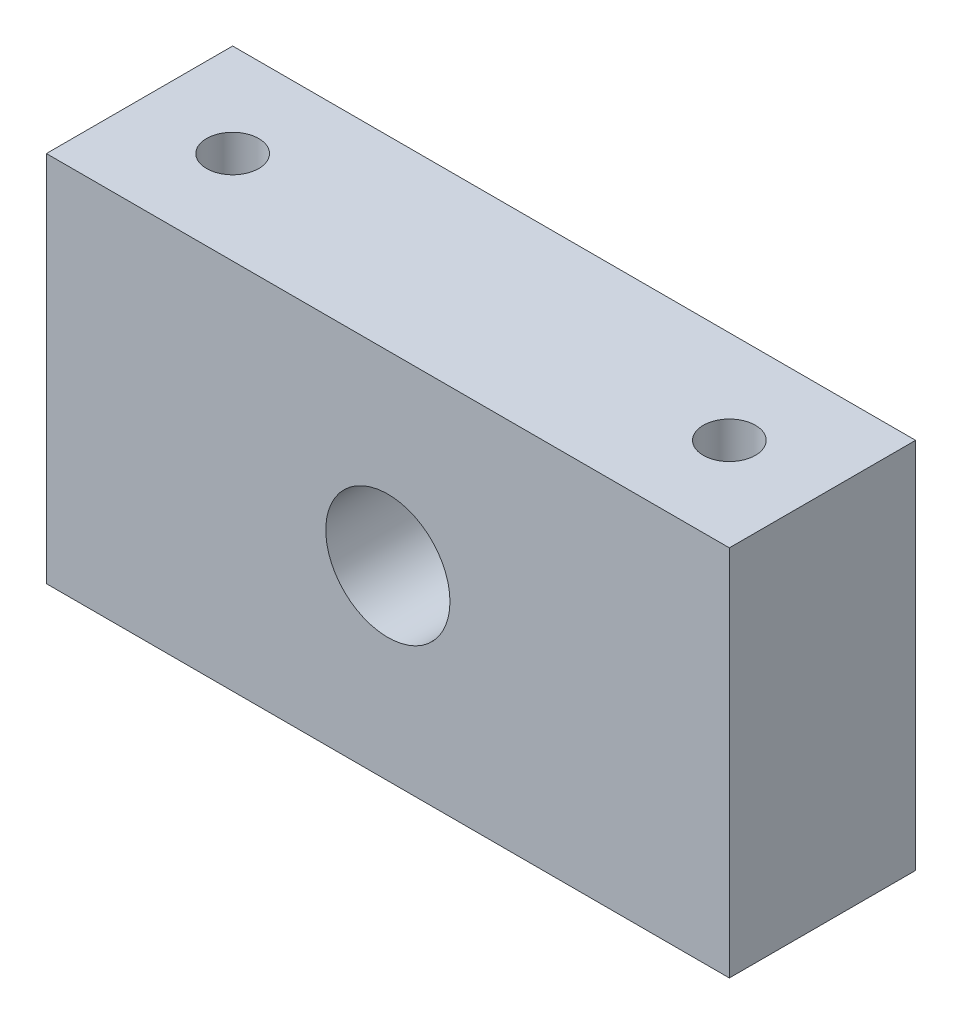
SolidWorks part; units mm, degrees
ref_plane "Front Plane" through (0, 0, 0) normal (0, 0, 1) x (1, 0, 0)
ref_plane "Top Plane" through (0, 0, 0) normal (0, 1, 0) x (1, 0, 0)
ref_plane "Right Plane" through (0, 0, 0) normal (1, 0, 0) x (0, 0, -1)
sketch "Sketch1" plane through (0, 0, 0) normal (0, 1, 0) x (1, 0, 0)
  line L1 (-27.5, 7.5) -> (27.5, 7.5)
  line L2 (-27.5, 7.5) -> (-27.5, -7.5)
  line L3 (-27.5, -7.5) -> (27.5, -7.5)
  line L4 (27.5, 7.5) -> (27.5, -7.5)
  line L5 (-27.5, 7.5) -> (27.5, -7.5) construction
  line L6 (-27.5, -7.5) -> (27.5, 7.5) construction
  point P0 (0, 0)
  dimension "D1" = 55
  dimension "D2" = 15
extrude "Boss-Extrude1" add sketch "Sketch1" along normal mid plane 30
sketch "Sketch3" plane through (0, 0, 7.5) normal (0, 0, 1) x (1, 0, 0)
  circle A0 centre (0, 0) radius 5
  dimension "D1" = 10
extrude "Cut-Extrude1" cut sketch "Sketch3" against normal through all
hole_wizard "M5 Tapped Hole1" positions "Sketch5" profile "Sketch6" tap size "M5" standard "ISO"
sketch "Sketch5" plane through (0, 15, 0) normal (0, 1, 0) x (1, 0, 0)
  point P0 (-20, 0)
  point P2 (20, 0)
  point P5 (0, 0)
  dimension "D1" = 20
  dimension "D2" = 20
sketch "Sketch6" plane through (-20, 15, 0) normal (1, 0, 0) x (0, 0, 1)
  line L0 (0, 0) -> (0, 21.2618)
  line L1 (0, 21.2618) -> (2.1, 20)
  line L2 (2.1, 20) -> (2.1, 0)
  line L5 (2.1, 0) -> (0, 0)
  line L10 (0, 21.2618) -> (-2.1, 20) construction
  line L11 (0, -6.35) -> (0, 107.95) construction
  dimension "Tap Drill Dia." = 4.2
  dimension "Tap Drill Depth" = 20
  dimension "Drill Angle" = 118
cosmetic thread "Hole Thread1" parameters "D1"=10, "D2"=5
cosmetic thread "Hole Thread2" parameters "D1"=10, "D2"=5
